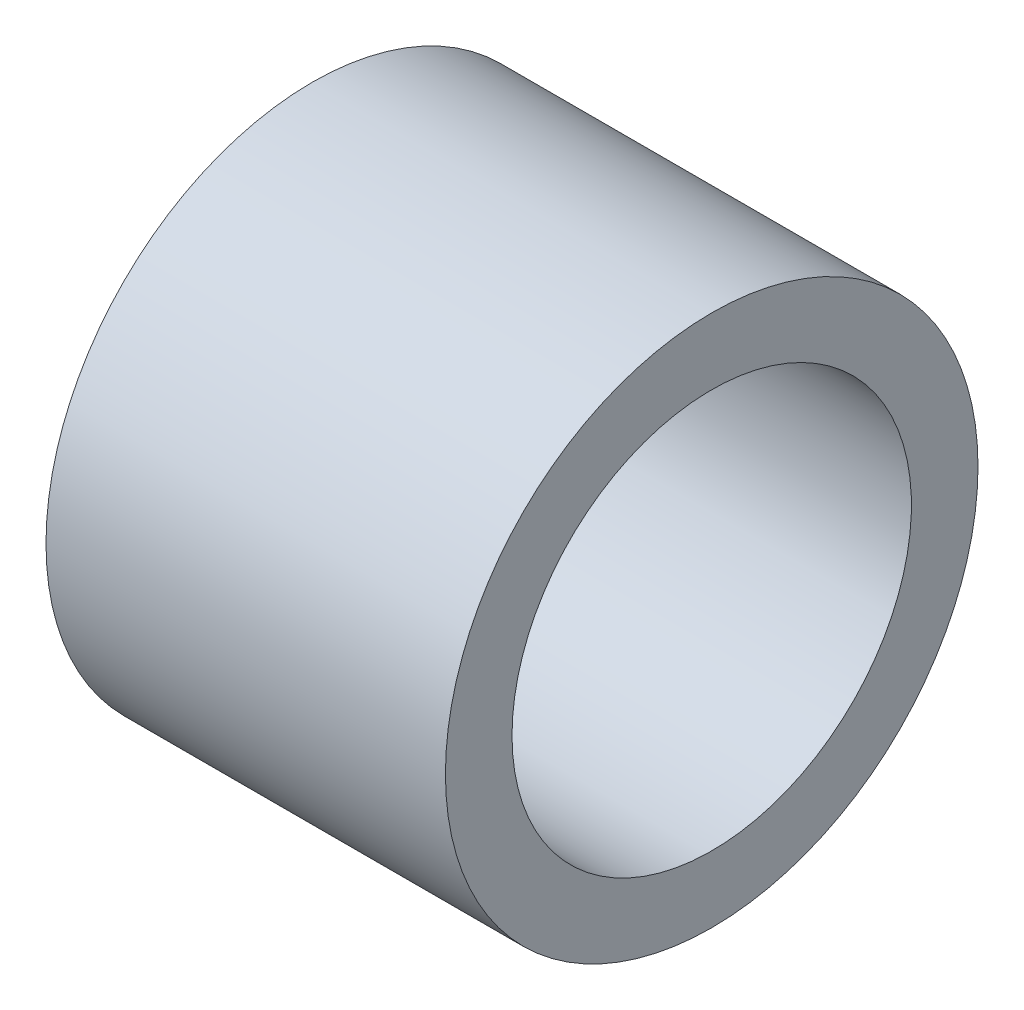
SolidWorks part; units mm, degrees
ref_plane "Front Plane" through (0, 0, 0) normal (0, 0, 1) x (1, 0, 0)
ref_plane "Top Plane" through (0, 0, 0) normal (0, 1, 0) x (1, 0, 0)
ref_plane "Right Plane" through (0, 0, 0) normal (1, 0, 0) x (0, 0, -1)
sketch "Sketch1" plane through (0, 0, 0) normal (1, 0, 0) x (0, 0, -1)
  circle A0 centre (0, 0) radius 9.525
  circle A1 centre (0, 0) radius 12.7
  dimension "D1" = 25.4
  dimension "D2" = 19.05
extrude "Boss-Extrude1" add sketch "Sketch1" along normal mid plane 19.05
